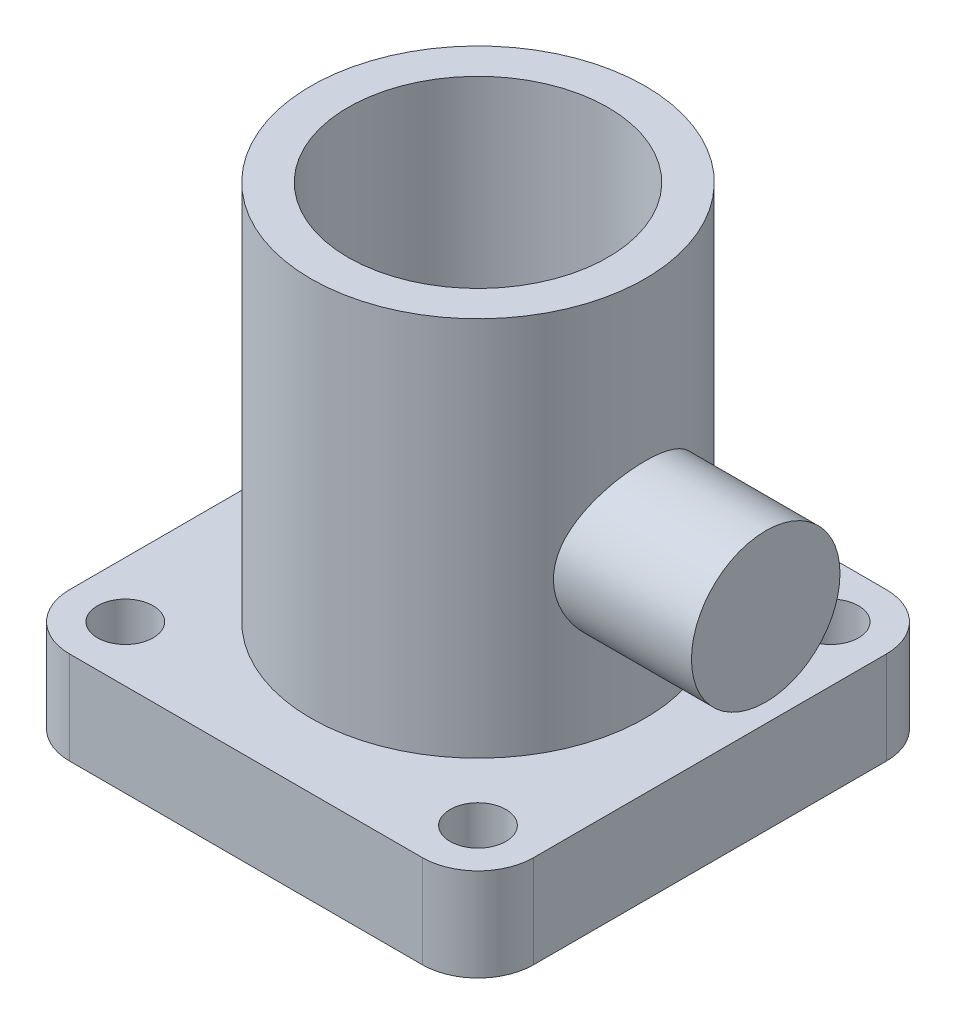
SolidWorks part; units mm, degrees
ref_plane "前视基准面" through (0, 0, 0) normal (0, 0, 1) x (1, 0, 0)
ref_plane "上视基准面" through (0, 0, 0) normal (0, 1, 0) x (1, 0, 0)
ref_plane "右视基准面" through (0, 0, 0) normal (1, 0, 0) x (0, 0, -1)
other "Configuration Table"
sketch "草图3" plane through (0, 0, 0) normal (0, 1, 0) x (1, 0, 0)
  line L1 (-25, -25) -> (25, -25)
  line L2 (-25, -25) -> (-25, 25)
  line L3 (-25, 25) -> (25, 25)
  line L4 (25, -25) -> (25, 25)
  line L5 (0, 25) -> (0, -25) construction
  line L6 (-25, 0) -> (25, 0) construction
  point P0 (0, 0)
  point P4 (44.6197, 33.7858)
  point P5 (0, 0)
extrude "凸台-拉伸1" add sketch "草图3" along normal blind 10
fillet "圆角7" radius 6 1 edges at (-25, 5, -25)
fillet "圆角8" radius 6 1 edges at (-25, 5, 25)
fillet "圆角9" radius 6 1 edges at (25, 5, 25)
fillet "圆角10" radius 6 1 edges at (25, 5, -25)
sketch "草图4" plane through (0, 10, 0) normal (0, 1, 0) x (1, 0, 0)
  circle A0 centre (-19, -19) radius 3
extrude "切除-拉伸1" cut sketch "草图4" against normal through all contours A0
sketch "草图6" plane through (0, 10, 0) normal (0, 1, 0) x (1, 0, 0)
  circle A0 centre (-19, 19) radius 3
extrude "切除-拉伸14" cut sketch "草图6" against normal through all
sketch "草图7" plane through (0, 10, 0) normal (0, 1, 0) x (1, 0, 0)
  circle A0 centre (19, 19) radius 3
extrude "切除-拉伸15" cut sketch "草图7" against normal through all
sketch "草图8" plane through (0, 10, 0) normal (0, 1, 0) x (1, 0, 0)
  circle A0 centre (19, -19) radius 3
extrude "切除-拉伸16" cut sketch "草图8" against normal through all
sketch "草图9" plane through (0, 0, 0) normal (0, 1, 0) x (1, 0, 0)
  circle A0 centre (0, 0) radius 18
extrude "凸台-拉伸4" add sketch "草图9" along normal blind 51
sketch "草图12" plane through (0, 0, 0) normal (1, 0, 0) x (0, 0, -1)
  circle A0 centre (0, 26) radius 8
  point P2 (0, 0)
extrude "凸台-拉伸5" add sketch "草图12" along normal blind 31 contours A0
sketch "草图10" plane through (0, 51, 0) normal (0, 1, 0) x (1, 0, 0)
  circle A0 centre (0, 0) radius 14
extrude "切除-拉伸17" cut sketch "草图10" against normal through all
sketch "草图16" plane through (31, 0, 0) normal (1, 0, 0) x (0, 0, -1)
  circle A1 centre (0, 26) radius 21
  arc A2 (-18.4193, 24.8017) -> (-18.4193, 27.1983) centre (-18.4193, 26) cw
